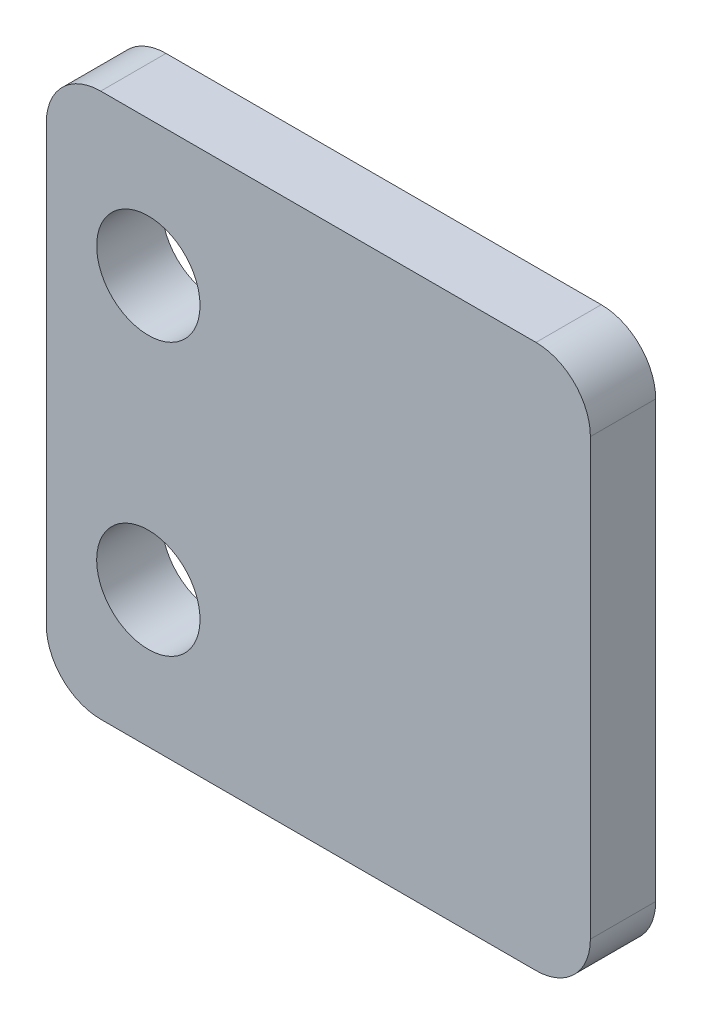
SolidWorks part; units mm, degrees
ref_plane "Front Plane" through (0, 0, 0) normal (0, 0, 1) x (1, 0, 0)
ref_plane "Top Plane" through (0, 0, 0) normal (0, 1, 0) x (1, 0, 0)
ref_plane "Right Plane" through (0, 0, 0) normal (1, 0, 0) x (0, 0, -1)
sketch "Sketch1" plane through (0, 0, 0) normal (0, 0, 1) x (1, 0, 0)
  line L0 (-71.12, 12.7) -> (3.048, 12.7) construction
  line L1 (-58.42, 12.7) -> (-83.82, 12.7)
  line L2 (-58.42, 12.7) -> (-58.42, -12.7)
  line L3 (-58.42, -12.7) -> (-83.82, -12.7)
  line L4 (-83.82, 12.7) -> (-83.82, -12.7)
  line L5 (3.048, -12.7) -> (-71.12, -12.7) construction
  line L6 (-71.12, 11.43) -> (-71.12, -11.43) construction
  point P8 (-71.12, 12.7)
  dimension "D1" = 12.7
extrude "Boss-Extrude1" add sketch "Sketch1" along normal blind 3.048 contours L2 L3 L4 L1
sketch "Sketch2" plane through (0, 0, 3.048) normal (0, 0, 1) x (1, 0, 0)
  line L0 (-1058.42, 0) -> (48941.58, 0) construction
  line L1 (-58.42, 12.7) -> (-58.42, -12.7) construction
  line L2 (-83.82, 12.7) -> (-83.82, -12.7) construction
  circle A0 centre (-79.0575, 6.35) radius 2.413
  circle A1 centre (-79.0575, -6.35) radius 2.413
  point P5 (-58.42, 0)
  dimension "D1" = 4.826
  dimension "D2" = 6.35
  dimension "D3" = 4.7625
fillet "Fillet1" radius 2.54 4 edges at (-83.82, -12.7, 1.524) (-58.42, -12.7, 1.524) (-58.42, 12.7, 1.524) (-83.82, 12.7, 1.524)
extrude "Cut-Extrude1" cut sketch "Sketch2" against normal up to next contours A0 | A1
